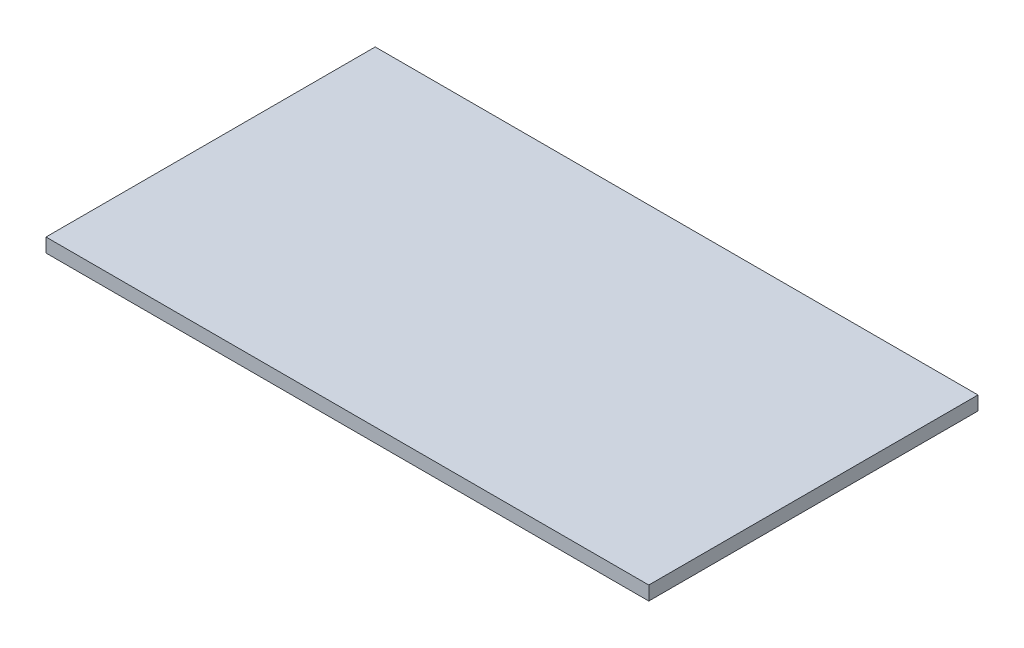
SolidWorks part; units mm, degrees
ref_plane "Front Plane" through (0, 0, 0) normal (0, 0, 1) x (1, 0, 0)
ref_plane "Top Plane" through (0, 0, 0) normal (0, 1, 0) x (1, 0, 0)
ref_plane "Right Plane" through (0, 0, 0) normal (1, 0, 0) x (0, 0, -1)
sketch "Sketch1" plane through (0, 0, 0) normal (0, 1, 0) x (1, 0, 0)
  line L1 (0, 0) -> (66.04, 0)
  line L2 (0, 0) -> (0, 36.068)
  line L3 (0, 36.068) -> (66.04, 36.068)
  line L4 (66.04, 0) -> (66.04, 36.068)
extrude "Boss-Extrude1" add sketch "Sketch1" along normal blind 1.524
